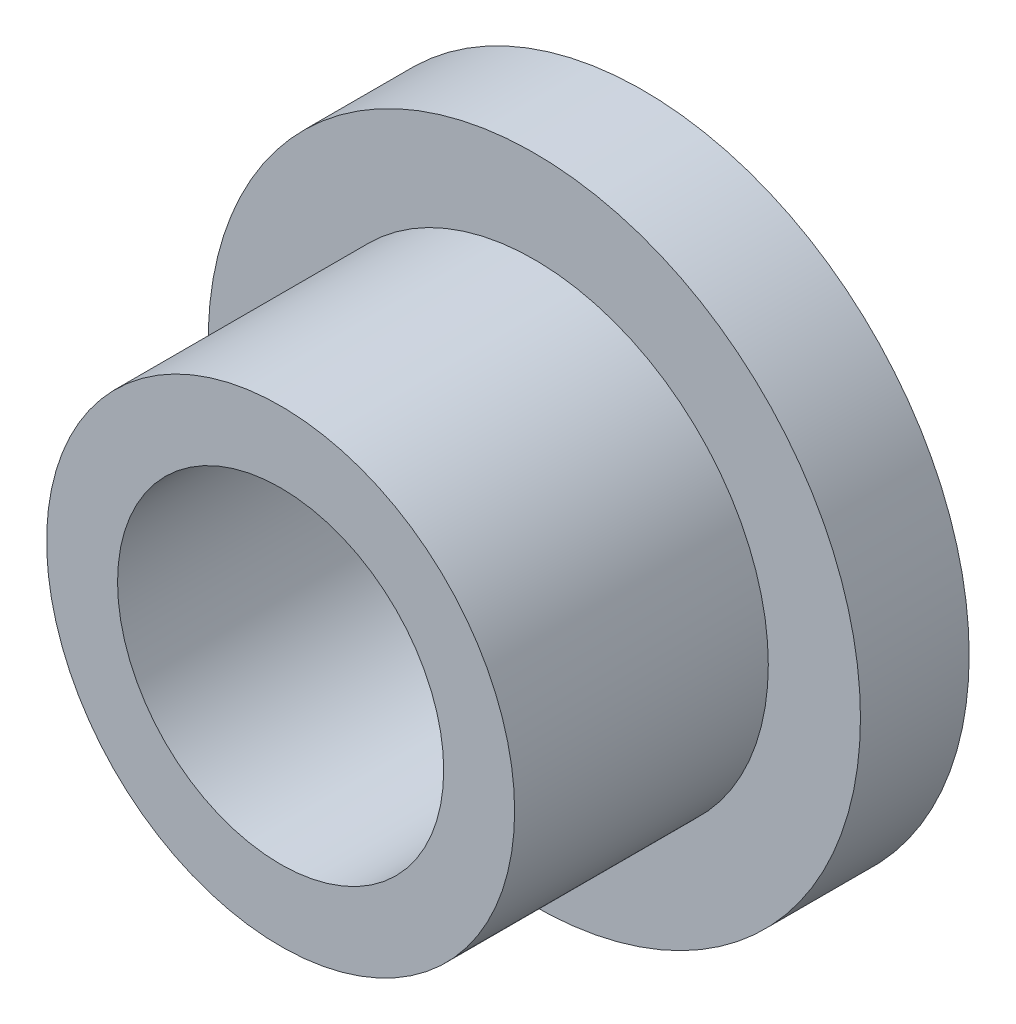
SolidWorks part; units mm, degrees
ref_plane "Спереди" through (0, 0, 0) normal (0, 0, 1) x (1, 0, 0)
ref_plane "Сверху" through (0, 0, 0) normal (0, 1, 0) x (1, 0, 0)
ref_plane "Справа" through (0, 0, 0) normal (1, 0, 0) x (0, 0, -1)
sketch "Эскиз1" plane through (0, 0, 0) normal (0, 0, 1) x (1, 0, 0)
  circle A0 centre (0, 0) radius 4.5
  circle A1 centre (0, 0) radius 9
extrude "Вытянуть1" add sketch "Эскиз1" along normal blind 10
sketch "Эскиз2" plane through (0, 0, 10) normal (0, 0, 1) x (1, 0, 0)
  circle A0 centre (0, 0) radius 9
  circle A1 centre (0, 0) radius 6.4572
extrude "Вырез-Вытянуть1" cut sketch "Эскиз2" against normal blind 7
